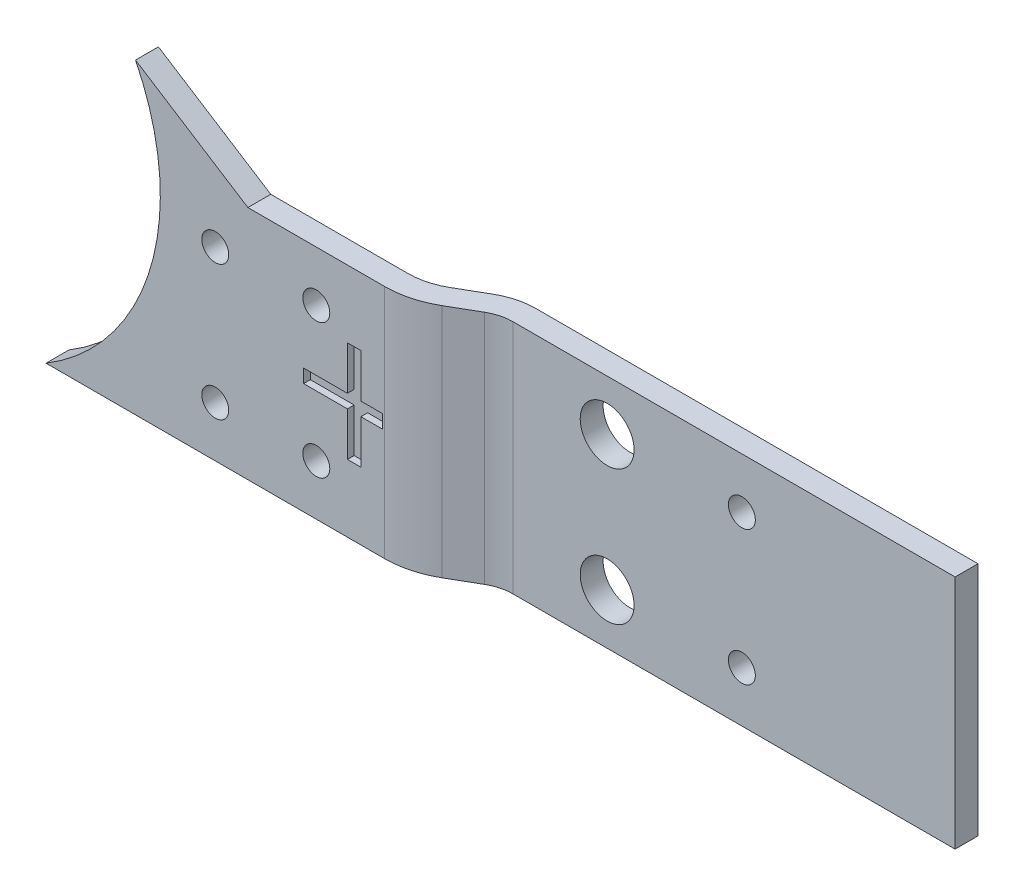
SolidWorks part; units mm, degrees
ref_plane "前视基准面" through (0, 0, 0) normal (0, 0, 1) x (1, 0, 0)
ref_plane "上视基准面" through (0, 0, 0) normal (0, 1, 0) x (1, 0, 0)
ref_plane "右视基准面" through (0, 0, 0) normal (1, 0, 0) x (0, 0, -1)
sketch "Sketch1" plane through (0, 0, 0) normal (0, 0, 1) x (1, 0, 0)
  line L0 (0, -30) -> (80, -30)
  line L1 (80, -30) -> (80, 5)
  line L2 (80, 5) -> (48, 5)
  line L4 (48, 5) -> (16.1141, 25.3049)
  arc A0 (16.1141, 25.3049) -> (0, -30) centre (0, 0) ccw
  dimension "D1" = 80
  dimension "D2" = 60
  dimension "D3" = 35
  dimension "D4" = 32
extrude "Boss-Extrude1" add sketch "Sketch1" along normal blind 3.4
sketch "Sketch2" plane through (0, 0, 3.4) normal (0, 0, 1) x (1, 0, 0)
  circle A0 centre (48, -12.5) radius 2.75
  circle A3 centre (48, -12.5) radius 2
  dimension "D2" = 5.5
sketch "Sketch3" plane through (0, 0, 3.4) normal (0, 0, 1) x (1, 0, 0)
  circle A0 centre (0, 0) radius 5
  dimension "D1" = 10
extrude "Cut-Extrude1" cut sketch "Sketch3" against normal blind 6
sketch "Sketch5" plane through (0, 0, 3.4) normal (0, 0, 1) x (1, 0, 0)
  line L0 (0, 20) -> (0, 0) construction
  line L1 (0, 0) -> (-18.1865, -10.5) construction
  arc A0 (0, 10) -> (-8.6603, -5) centre (0, 0) ccw
  arc A2 (0, 18) -> (-15.5885, -9) centre (0, 0) ccw
  arc A3 (-8.6603, -5) -> (-15.5885, -9) centre (-12.1244, -7) cw
  arc A4 (0, 18) -> (0, 10) centre (0, 14) cw
  point P4 (0, 18)
  point P6 (0, 10)
  point P8 (-8.6603, -5)
  point P9 (-15.5885, -9)
  dimension "D1" = 120
  dimension "D2" = 21
extrude "Cut-Extrude2" cut sketch "Sketch5" against normal blind 10
sketch "Sketch6" plane through (0, 0, 0) normal (0, 0, -1) x (-1, 0, 0)
  circle A0 centre (0, 0) radius 35
extrude "Cut-Extrude3" cut sketch "Sketch6" against normal blind 10
sketch "Sketch7" plane through (0, 0, 3.4) normal (0, 0, 1) x (1, 0, 0)
  line L0 (62.7754, -13.5) -> (62.7754, -20)
  line L1 (64.7754, -5) -> (62.7754, -5)
  line L2 (64.7754, -5) -> (64.7754, -11.5)
  line L3 (64.7754, -20) -> (62.7754, -20)
  line L4 (62.7754, -5) -> (62.7754, -11.5)
  line L5 (80, 5) -> (48, 5) construction
  line L7 (80, -30) -> (80, 5) construction
  line L8 (62.7754, -11.5) -> (56.2754, -11.5)
  line L9 (71.2754, -11.5) -> (64.7754, -11.5)
  line L10 (71.2754, -11.5) -> (71.2754, -13.5)
  line L11 (71.2754, -13.5) -> (64.7754, -13.5)
  line L12 (56.2754, -11.5) -> (56.2754, -13.5)
  line L17 (62.7754, -13.5) -> (56.2754, -13.5)
  line L18 (63.9087, -13.5) -> (63.642, -13.5)
  line L19 (64.7754, -13.5) -> (64.7754, -20)
  point P0 (63.9087, -12.5)
  point P9 (80, -12.5)
  point P10 (63.7754, -13.5)
  dimension "D1" = 15
  dimension "D2" = 2
  dimension "D3" = 0
  dimension "D4" = 2
  dimension "D5" = 15
  dimension "D6" = 16.5
extrude "Cut-Extrude4" cut sketch "Sketch7" against normal blind 1
sketch "Sketch8" plane through (0, 0, 0) normal (0, 0, -1) x (-1, 0, 0)
  line L0 (-80, 5) -> (-48, 5) construction
  line L1 (-80, -30) -> (-68, -30)
  line L2 (-80, -30) -> (-80, 5)
  line L3 (-80, 5) -> (-68, 5)
  line L4 (-68, -30) -> (-68, 5)
  dimension "D1" = 20
extrude "Cut-Extrude5" cut sketch "Sketch8" against normal up to next
sketch "Sketch9" plane through (0, 5, 0) normal (0, 1, 0) x (1, 0, 0)
  line L0 (68, 0) -> (68.3205, 0)
  line L1 (83, 5) -> (148, 5)
  line L2 (73.3205, 1.3397) -> (77.3397, 3.6603)
  line L3 (68, -3.4) -> (68.3205, -3.4)
  line L4 (75.0205, -1.6047) -> (79.0397, 0.7158)
  line L5 (82.3397, 5) -> (83, 5)
  line L6 (68, 0) -> (48, 0) construction
  line L7 (82.3397, 1.6) -> (83, 1.6)
  line L8 (83, 1.6) -> (148, 1.6)
  line L9 (68, 0) -> (68, -3.4)
  line L10 (148, 1.6) -> (148, 5)
  arc A0 (77.3397, 3.6603) -> (82.3397, 5) centre (82.3397, -5) cw
  arc A1 (68.3205, 0) -> (73.3205, 1.3397) centre (68.3205, 10) ccw
  arc A2 (68.3205, -3.4) -> (75.0205, -1.6047) centre (68.3205, 10) ccw
  arc A3 (79.0397, 0.7158) -> (82.3397, 1.6) centre (82.3397, -5) cw
  point P11 (68, 0)
  dimension "D1" = 15
  dimension "D4" = 10
  dimension "D2" = 5
  dimension "D3" = 150
  dimension "D6" = 65
  dimension "D5" = 3.4
extrude "Boss-Extrude2" add sketch "Sketch9" against normal up to surface (35 mm away) up to face at (43.0139, -30, 1.7)
sketch "Sketch10" plane through (0, 0, -5) normal (0, 0, -1) x (-1, 0, 0)
  line L0 (-96.3397, 5) -> (-96.3397, -30) construction
  line L1 (-148, 5) -> (-82.3397, 5) construction
  line L2 (-82.3397, -30) -> (-148, -30) construction
  line L3 (-82.3397, -30) -> (-82.3397, 5) construction
  line L4 (-82.3397, -12.5) -> (-106.6658, -12.5) construction
  circle A0 centre (-96.3397, -2.5) radius 4
  circle A1 centre (-96.3397, -22.5) radius 4
  dimension "D2" = 10
  dimension "D1" = 14
extrude "Cut-Extrude6" cut sketch "Sketch10" against normal blind 10
sketch "Sketch11" plane through (0, 0, 0) normal (0, 0, -1) x (-1, 0, 0)
  line L0 (-68.3205, -30) -> (-68.3205, 5) construction
  circle A0 centre (-58.1603, -22.5) radius 2
  circle A1 centre (-58.1603, -2.5) radius 2
  circle A4 centre (-43.1603, -22.5) radius 2
  circle A5 centre (-43.1603, -2.5) radius 2
  point P6 (-68.3205, -12.5)
  dimension "D1" = 4
  dimension "D4" = 15
  dimension "D5" = 15
  dimension "D2" = 10
  dimension "D3" = 10
extrude "Cut-Extrude7" cut sketch "Sketch11" against normal up to next
sketch "Sketch12" plane through (0, 0, -5) normal (0, 0, -1) x (-1, 0, 0)
  line L0 (-60.1603, -22.5) -> (-138.46, -22.5) construction
  line L1 (-58.1603, -2.5) -> (-138.46, -2.5) construction
  circle A0 centre (-116.3397, -22.5) radius 2
  circle A1 centre (-116.3397, -2.5) radius 2
  circle A2 centre (-58.1603, -22.5) radius 2 construction
  circle A3 centre (-96.3397, -22.5) radius 4 construction
  circle A4 centre (-96.3397, -2.5) radius 4 construction
  dimension "D1" = 20
  dimension "D2" = 20
extrude "Cut-Extrude8" cut sketch "Sketch12" against normal up to next
